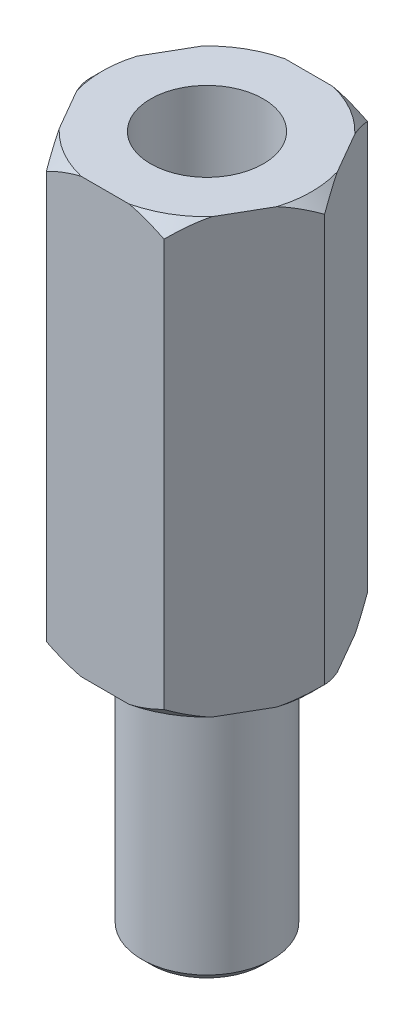
SolidWorks part; units mm, degrees
material "Brass"
ref_plane "Front" through (0, 0, 0) normal (0, 0, 1) x (1, 0, 0)
ref_plane "Top" through (0, 0, 0) normal (0, 1, 0) x (1, 0, 0)
ref_plane "Right" through (0, 0, 0) normal (1, 0, 0) x (0, 0, -1)
sketch "Sketch1" plane through (0, 0, 0) normal (0, 1, 0) x (1, 0, 0)
  line L1 (-2.7135, 0) -> (-1.3568, -2.35)
  line L2 (-1.3568, -2.35) -> (1.3568, -2.35)
  line L3 (1.3568, -2.35) -> (2.7135, 0)
  line L4 (2.7135, 0) -> (1.3568, 2.35)
  line L5 (1.3568, 2.35) -> (-1.3568, 2.35)
  line L6 (-1.3568, 2.35) -> (-2.7135, 0)
  circle A0 centre (0, 0) radius 1.3
  circle A1 centre (0, 0) radius 2.35 construction
  dimension "D2" = 2.6
  dimension "D1" = 4.7
extrude "Boss-Extrude1" add sketch "Sketch1" along normal blind 10
cosmetic thread "Cosmetic Thread2" parameters "D2"=3.5
sketch "Sketch2" plane through (0, 0, 0) normal (0, -1, 0) x (1, 0, 0)
  circle A0 centre (0, 0) radius 1.5
  dimension "D1" = 3
extrude "Boss-Extrude2" add sketch "Sketch2" along normal blind 6 and the other way blind 2
cosmetic thread "Cosmetic Thread1" parameters "D2"=2.439
chamfer "Chamfer1" distance 0.2 angle 45 1 edges at (0, -6, -1.5)
sketch "Sketch6" plane through (0, 0, 0) normal (0, 0, 1) x (1, 0, 0)
  line L0 (0, 0) -> (0, 8.532) construction
  line L1 (-2.7135, 5) -> (-7.8723, 5) construction
  line L2 (-2.7135, 10) -> (-2.7135, 0) construction
  line L3 (-2.7135, 10) -> (-2.7135, 9.7)
  line L4 (-2.7135, 9.7) -> (-2.4135, 10)
  line L5 (-2.4135, 10) -> (-2.7135, 10)
  line L6 (-2.4135, 0) -> (-2.7135, 0)
  line L7 (-2.7135, 0.3) -> (-2.4135, 0)
  line L8 (-2.7135, 0) -> (-2.7135, 0.3)
  dimension "D1" = 45
  dimension "D2" = 0.3
revolve "Cut-Revolve1" cut sketch "Sketch6" angle 360 about L0
